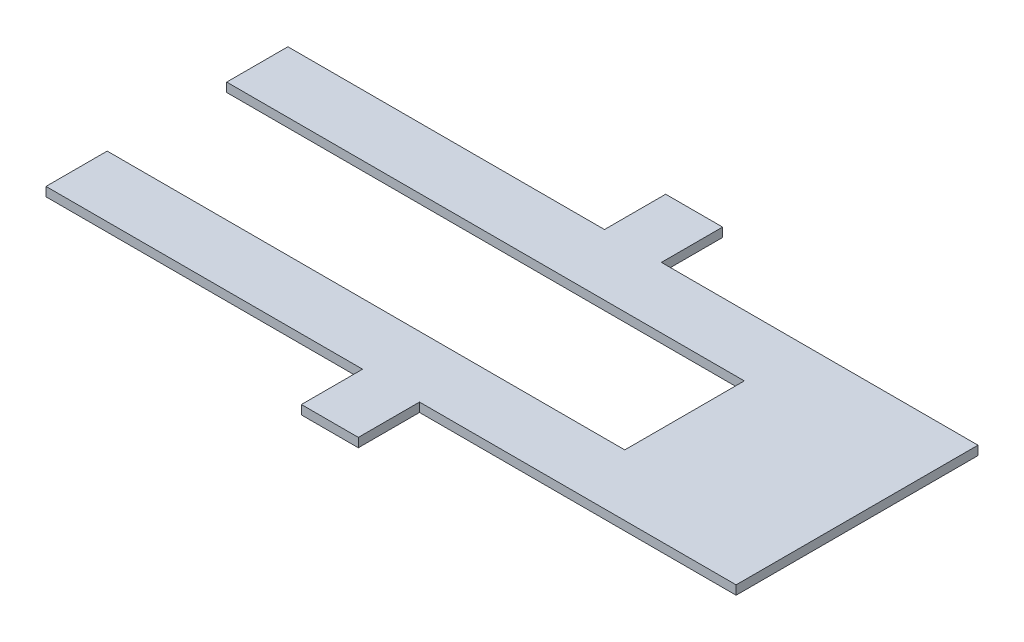
SolidWorks part; units mm, degrees
ref_plane "Front Plane" through (0, 0, 0) normal (0, 0, 1) x (1, 0, 0)
ref_plane "Top Plane" through (0, 0, 0) normal (0, 1, 0) x (1, 0, 0)
ref_plane "Right Plane" through (0, 0, 0) normal (1, 0, 0) x (0, 0, -1)
sketch "Sketch1" plane through (0, 0, 0) normal (0, 1, 0) x (1, 0, 0)
  line L0 (-485.1918, 167.6708) -> (-40.1918, 167.6708)
  line L1 (484.8082, 167.6708) -> (484.8082, -172.3292)
  line L3 (-485.1918, 81.6708) -> (-485.1918, -86.3292) construction
  line L4 (0, -2.3292) -> (-485.1918, 167.6708) construction
  line L5 (39.8082, -172.3292) -> (484.8082, -172.3292)
  line L6 (-485.1918, -172.3292) -> (0, -2.3292) construction
  line L7 (39.8082, -258.3292) -> (39.8082, -172.3292)
  line L8 (0, -2.3292) -> (484.8082, -172.3292) construction
  line L9 (-0.1918, 167.6708) -> (0, 81.6708) construction
  line L10 (-242.5959, 81.6708) -> (-485.1918, 81.6708) construction
  line L11 (0, -2.3292) -> (484.8082, 167.6708) construction
  line L12 (-242.5959, 81.6708) -> (484.8082, 81.6708) construction
  line L13 (-485.1918, 167.6708) -> (-485.1918, 81.6708)
  line L14 (-0.1918, 167.6708) -> (484.8082, -2.3292) construction
  line L15 (484.8082, 167.6708) -> (0, 81.6708) construction
  line L16 (-0.1918, 167.6708) -> (-0.1918, 285.4716) construction
  line L17 (242.3082, 124.6708) -> (242.3082, -2.3292) construction
  line L18 (-485.1918, 81.6708) -> (242.3082, 81.6708) construction
  line L19 (242.3082, 81.6708) -> (242.3082, -2.3292) construction
  line L20 (-485.1918, 81.6708) -> (242.3082, 81.6708)
  line L21 (242.3082, 81.6708) -> (242.3082, -86.3292)
  line L24 (-40.1918, 253.6708) -> (39.8082, 253.6708)
  line L25 (39.8082, 253.6708) -> (39.8082, 167.6708)
  line L26 (-40.1918, 253.6708) -> (-40.1918, 167.6708)
  line L27 (39.8082, 167.6708) -> (484.8082, 167.6708)
  line L28 (-40.1918, 167.6708) -> (39.8082, 167.6708) construction
  line L29 (484.8082, 167.6708) -> (484.8082, -2.3292) construction
  line L30 (484.8082, -2.3292) -> (0, -2.3292) construction
  line L31 (0, -2.3292) -> (-485.1918, -2.3292) construction
  line L32 (0, 81.6708) -> (0, -2.3292) construction
  line L33 (0, -2.3292) -> (0, -86.3292) construction
  line L34 (0, -86.3292) -> (-0.1918, -172.3292) construction
  line L35 (-485.1918, 124.6708) -> (484.8082, 124.6708) construction
  line L36 (239.5523, -86.3292) -> (484.8082, -86.3292) construction
  line L37 (-40.1918, -258.3292) -> (39.8082, -258.3292)
  line L38 (-40.1918, -258.3292) -> (-40.1918, -172.3292)
  line L39 (-485.1918, -172.3292) -> (-40.1918, -172.3292)
  line L40 (-485.1918, -172.3292) -> (-485.1918, -86.3292)
  line L41 (-485.1918, -86.3292) -> (242.3082, -86.3292)
  point P13 (-0.1918, 253.6708)
  dimension "D1" = 86
  dimension "D2" = 970
  dimension "D3" = 340
  dimension "D5" = 86
  dimension "D6" = 40
extrude "Boss-Extrude1" add sketch "Sketch1" along normal blind 12.7 contours L1 L5 L7 L37 L38 L39 L40 L41 L21 L20 L13 L0 L26 L24 L25 L27
